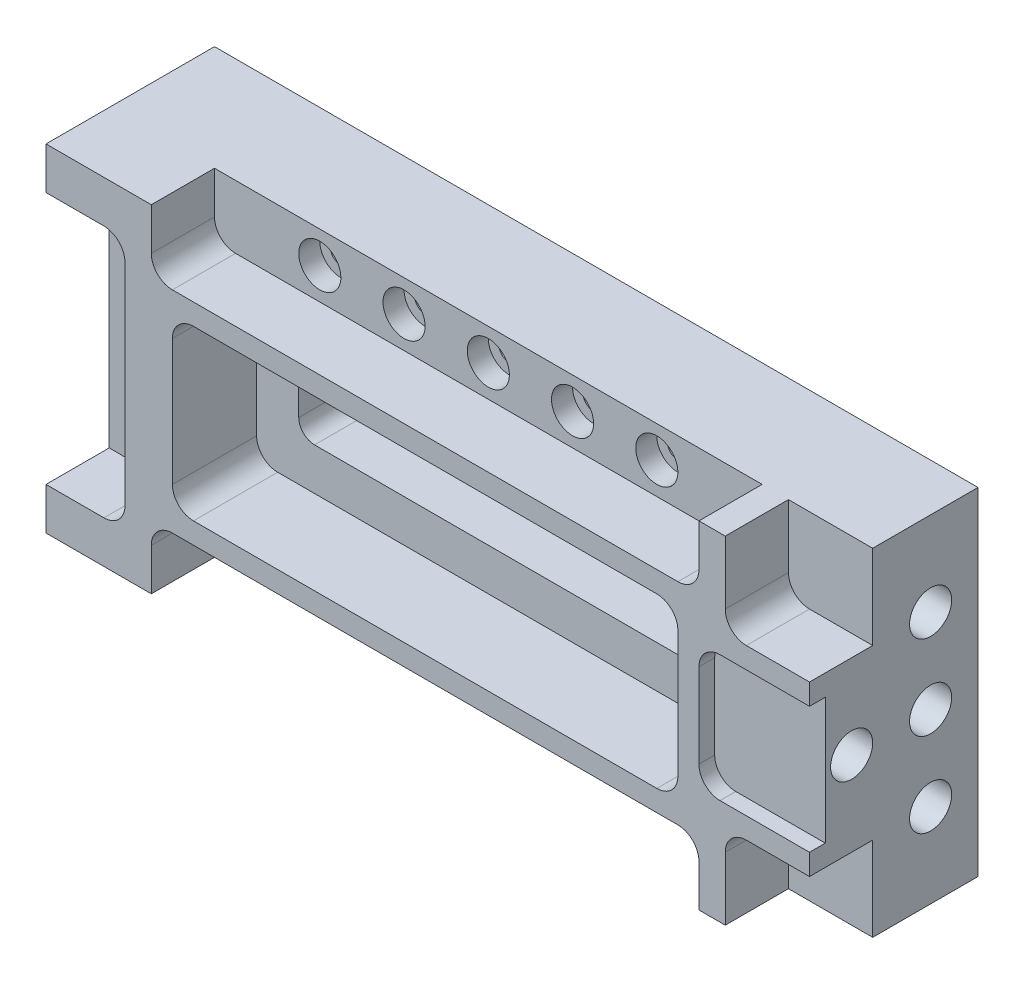
SolidWorks part; units mm, degrees
ref_plane "Plane1" through (0, 0, 0) normal (0, 0, 1) x (1, 0, 0)
ref_plane "Plane2" through (0, 0, 0) normal (0, 1, 0) x (1, 0, 0)
ref_plane "Plane3" through (0, 0, 0) normal (1, 0, 0) x (0, 0, -1)
sketch "Sketch1" plane through (0, 0, 0) normal (0, 0, 1) x (1, 0, 0)
  line L1 (-114.3, 50.8) -> (115.8875, 50.8)
  line L2 (-114.3, 50.8) -> (-114.3, -50.8)
  line L3 (-114.3, -50.8) -> (115.8875, -50.8)
  line L4 (115.8875, 50.8) -> (115.8875, -50.8)
extrude "Base-Extrude" add sketch "Sketch1" along normal blind 50.8
sketch "Sketch2" plane through (0, 0, 50.8) normal (0, 0, 1) x (1, 0, 0)
  line L1 (-69.85, 25.4) -> (69.85, 25.4)
  line L2 (-76.2, 19.05) -> (-76.2, -19.05)
  line L3 (-69.85, -25.4) -> (69.85, -25.4)
  line L4 (76.2, 19.05) -> (76.2, -19.05)
  arc A0 (-76.2, 19.05) -> (-69.85, 25.4) centre (-69.85, 19.05) cw
  arc A1 (-69.85, -25.4) -> (-76.2, -19.05) centre (-69.85, -19.05) cw
  arc A2 (76.2, -19.05) -> (69.85, -25.4) centre (69.85, -19.05) cw
  arc A3 (76.2, 19.05) -> (69.85, 25.4) centre (69.85, 19.05) ccw
  dimension "D1" = 6.35
extrude "Cut-Extrude1" cut sketch "Sketch2" against normal blind 25.4
sketch "Sketch3" plane through (0, 0, 50.8) normal (0, 0, 1) x (1, 0, 0)
  line L1 (136.525, 61.9125) -> (90.4875, 61.9125)
  line L2 (136.525, 61.9125) -> (136.525, 25.4)
  line L3 (136.525, 25.4) -> (96.8375, 25.4)
  line L4 (90.4875, 61.9125) -> (90.4875, 31.75)
  line L5 (136.525, -57.15) -> (90.4875, -57.15)
  line L6 (136.525, -57.15) -> (136.525, -25.4)
  line L7 (136.525, -25.4) -> (96.8375, -25.4)
  line L8 (90.4875, -57.15) -> (90.4875, -31.75)
  arc A0 (90.4875, -31.75) -> (96.8375, -25.4) centre (96.8375, -31.75) cw
  arc A1 (90.4875, 31.75) -> (96.8375, 25.4) centre (96.8375, 31.75) ccw
  dimension "D1" = 6.35
extrude "Cut-Extrude2" cut sketch "Sketch3" against normal blind 19.05
sketch "Sketch4" plane through (0, 0, 50.8) normal (0, 0, 1) x (1, 0, 0)
  line L1 (-120.65, 38.1) -> (-96.8375, 38.1)
  line L2 (-120.65, 38.1) -> (-120.65, -38.1)
  line L3 (-120.65, -38.1) -> (-96.8375, -38.1)
  line L4 (-90.4875, 31.75) -> (-90.4875, -31.75)
  arc A0 (-90.4875, -31.75) -> (-96.8375, -38.1) centre (-96.8375, -31.75) cw
  arc A1 (-90.4875, 31.75) -> (-96.8375, 38.1) centre (-96.8375, 31.75) ccw
  dimension "D1" = 6.35
extrude "Cut-Extrude3" cut sketch "Sketch4" against normal blind 19.05
sketch "Sketch5" plane through (-114.3, 0, 0) normal (-1, 0, 0) x (0, 0, 1)
  circle A0 centre (14.2875, 0) radius 6.35
  circle A1 centre (14.2875, -25.4) radius 6.35
  circle A2 centre (14.2875, 25.4) radius 6.35
extrude "Cut-Extrude4" cut sketch "Sketch5" against normal blind 25.4
chamfer "Chamfer2" distance 1.5748 angle 45
sketch "Sketch6" plane through (115.8875, 0, 0) normal (1, 0, 0) x (0, 0, -1)
  circle A0 centre (-38.1, 0) radius 6.35
  circle A1 centre (-14.2875, 0) radius 6.35
  circle A2 centre (-14.2875, 25.4) radius 6.35
  circle A3 centre (-14.2875, -25.4) radius 6.35
extrude "Cut-Extrude5" cut sketch "Sketch6" against normal blind 25.4
sketch "Sketch7" plane through (0, 0, 25.4) normal (0, 0, 1) x (1, 0, 0)
  line L1 (-58.7375, 12.7) -> (58.7375, 12.7)
  line L2 (-63.5, 7.9375) -> (-63.5, -7.9375)
  line L3 (-58.7375, -12.7) -> (58.7375, -12.7)
  line L4 (63.5, 7.9375) -> (63.5, -7.9375)
  arc A0 (-58.7375, -12.7) -> (-63.5, -7.9375) centre (-58.7375, -7.9375) cw
  arc A1 (-63.5, 7.9375) -> (-58.7375, 12.7) centre (-58.7375, 7.9375) cw
  arc A2 (63.5, 7.9375) -> (58.7375, 12.7) centre (58.7375, 7.9375) ccw
  arc A3 (63.5, -7.9375) -> (58.7375, -12.7) centre (58.7375, -7.9375) cw
  dimension "D1" = 4.7625
extrude "Cut-Extrude6" cut sketch "Sketch7" against normal blind 19.05
sketch "Sketch8" plane through (0, 0, 6.35) normal (0, 0, 1) x (1, 0, 0)
  circle A0 centre (-50.8, 6.35) radius 3.175
  circle A1 centre (-38.1, 6.35) radius 3.175
  circle A2 centre (-25.4, 6.35) radius 3.175
  circle A3 centre (-12.7, 6.35) radius 3.175
  circle A4 centre (0, 6.35) radius 3.175
  circle A5 centre (12.7, 6.35) radius 3.175
  circle A6 centre (25.4, 6.35) radius 3.175
  circle A7 centre (38.1, 6.35) radius 3.175
  circle A8 centre (50.8, 6.35) radius 3.175
  circle A9 centre (-50.8, -6.35) radius 3.175
  circle A10 centre (-38.1, -6.35) radius 3.175
  circle A11 centre (-25.4, -6.35) radius 3.175
  circle A12 centre (-12.7, -6.35) radius 3.175
  circle A13 centre (0, -6.35) radius 3.175
  circle A14 centre (12.7, -6.35) radius 3.175
  circle A15 centre (25.4, -6.35) radius 3.175
  circle A16 centre (38.1, -6.35) radius 3.175
  circle A17 centre (50.8, -6.35) radius 3.175
extrude "Cut-Extrude7" cut sketch "Sketch8" against normal through all
sketch "Sketch9" plane through (0, 0, 50.8) normal (0, 0, 1) x (1, 0, 0)
  line L1 (-82.55, 63.5) -> (82.55, 63.5)
  line L2 (-82.55, 63.5) -> (-82.55, 38.1)
  line L3 (-76.2, 31.75) -> (76.2, 31.75)
  line L4 (82.55, 63.5) -> (82.55, 38.1)
  line L5 (-82.55, -60.325) -> (82.55, -60.325)
  line L6 (-82.55, -60.325) -> (-82.55, -38.1)
  line L7 (-76.2, -31.75) -> (76.2, -31.75)
  line L8 (82.55, -60.325) -> (82.55, -38.1)
  arc A0 (-76.2, 31.75) -> (-82.55, 38.1) centre (-76.2, 38.1) cw
  arc A1 (82.55, 38.1) -> (76.2, 31.75) centre (76.2, 38.1) cw
  arc A2 (82.55, -38.1) -> (76.2, -31.75) centre (76.2, -38.1) ccw
  arc A3 (-76.2, -31.75) -> (-82.55, -38.1) centre (-76.2, -38.1) ccw
  dimension "D1" = 6.35
extrude "Cut-Extrude8" cut sketch "Sketch9" against normal blind 19.05
sketch "Sketch10" plane through (0, 0, 31.75) normal (0, 0, 1) x (1, 0, 0)
  circle A0 centre (0, -41.275) radius 3.175
  circle A1 centre (25.4, -41.275) radius 3.175
  circle A2 centre (50.8, -41.275) radius 3.175
  circle A3 centre (-25.4, -41.275) radius 3.175
  circle A4 centre (-50.8, -41.275) radius 3.175
  circle A5 centre (0, 41.275) radius 3.175
  circle A6 centre (25.4, 41.275) radius 3.175
  circle A7 centre (50.8, 41.275) radius 3.175
  circle A8 centre (-25.4, 41.275) radius 3.175
  circle A9 centre (-50.8, 41.275) radius 3.175
extrude "Cut-Extrude9" cut sketch "Sketch10" against normal through all
sketch "Sketch11" plane through (0, 0, 31.75) normal (0, 0, 1) x (1, 0, 0)
  circle A0 centre (-50.8, 41.275) radius 6.35
  circle A1 centre (-25.4, 41.275) radius 6.35
  circle A2 centre (0, 41.275) radius 6.35
  circle A3 centre (25.4, 41.275) radius 6.35
  circle A4 centre (50.8, 41.275) radius 6.35
  circle A5 centre (-50.8, -41.275) radius 6.35
  circle A6 centre (-25.4, -41.275) radius 6.35
  circle A7 centre (0, -41.275) radius 6.35
  circle A8 centre (25.4, -41.275) radius 6.35
  circle A9 centre (50.8, -41.275) radius 6.35
extrude "Cut-Extrude10" cut sketch "Sketch11" against normal blind 6.35
sketch "Sketch12" plane through (0, 0, 50.8) normal (0, 0, 1) x (1, 0, 0)
  line L1 (88.9, 19.05) -> (123.825, 19.05)
  line L2 (82.55, 12.7) -> (82.55, -12.7)
  line L3 (88.9, -19.05) -> (123.825, -19.05)
  line L4 (123.825, 19.05) -> (123.825, -19.05)
  arc A0 (82.55, 12.7) -> (88.9, 19.05) centre (88.9, 12.7) cw
  arc A1 (88.9, -19.05) -> (82.55, -12.7) centre (88.9, -12.7) cw
  dimension "D1" = 6.35
extrude "Cut-Extrude11" cut sketch "Sketch12" against normal blind 4.7498
